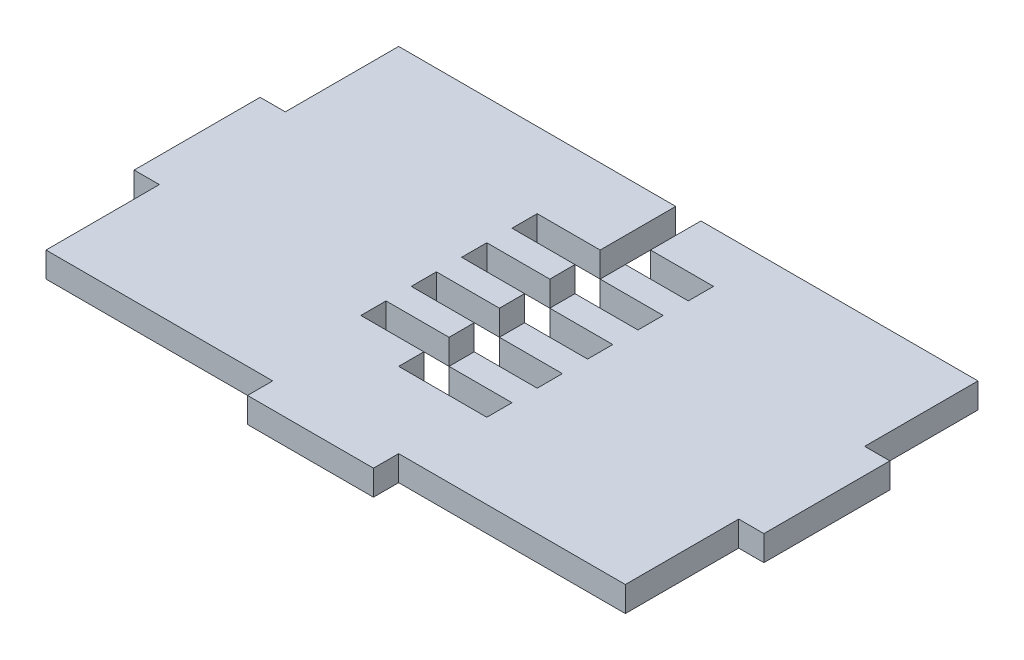
SolidWorks part; units mm, degrees
ref_plane "前视基准面" through (0, 0, 0) normal (0, 0, 1) x (1, 0, 0)
ref_plane "上视基准面" through (0, 0, 0) normal (0, 1, 0) x (1, 0, 0)
ref_plane "右视基准面" through (0, 0, 0) normal (1, 0, 0) x (0, 0, -1)
sketch "草图1" plane through (0, 0, 0) normal (0, 1, 0) x (1, 0, 0)
  line L1 (0, 0) -> (92, 0)
  line L2 (0, 0) -> (0, 56)
  line L3 (0, 56) -> (92, 56)
  line L4 (92, 0) -> (92, 56)
  line L5 (0, 38) -> (-4, 38)
  line L6 (0, 38) -> (0, 18)
  line L7 (0, 18) -> (-4, 18)
  line L8 (-4, 38) -> (-4, 18)
  line L9 (92, 38) -> (96, 38)
  line L10 (92, 38) -> (92, 18)
  line L11 (92, 18) -> (96, 18)
  line L12 (96, 38) -> (96, 18)
  line L13 (44, 56) -> (48, 56)
  line L14 (44, 56) -> (44, 12)
  line L15 (44, 12) -> (48, 12)
  line L16 (48, 56) -> (48, 12)
  line L22 (48, 34) -> (48, 36)
  line L34 (44, 44) -> (44, 40)
  line L42 (44, 28) -> (44, 24)
  line L45 (56, 0) -> (36, 0)
  line L46 (56, 0) -> (56, -4)
  line L47 (56, -4) -> (36, -4)
  line L48 (36, 0) -> (36, -4)
  line L50 (48, 24) -> (48, 12)
  line L53 (48, 16) -> (58, 16)
  line L54 (48, 16) -> (48, 12)
  line L55 (48, 12) -> (58, 12)
  line L56 (58, 16) -> (58, 12)
  line L57 (48, 20) -> (58, 20)
  line L58 (48, 20) -> (48, 24)
  line L59 (48, 24) -> (58, 24)
  line L60 (58, 20) -> (58, 24)
  line L61 (48, 32) -> (58, 32)
  line L62 (48, 32) -> (48, 28)
  line L63 (48, 28) -> (58, 28)
  line L64 (58, 32) -> (58, 28)
  line L65 (48, 40) -> (58, 40)
  line L66 (48, 40) -> (48, 36)
  line L67 (48, 36) -> (58, 36)
  line L68 (58, 40) -> (58, 36)
  line L69 (48, 48) -> (58, 48)
  line L70 (48, 48) -> (48, 44)
  line L71 (48, 44) -> (58, 44)
  line L72 (58, 48) -> (58, 44)
  line L73 (44, 44) -> (34, 44)
  line L74 (44, 44) -> (44, 40)
  line L75 (44, 40) -> (34, 40)
  line L76 (34, 44) -> (34, 40)
  line L77 (44, 36) -> (34, 36)
  line L78 (44, 36) -> (44, 32)
  line L79 (44, 32) -> (34, 32)
  line L80 (34, 36) -> (34, 32)
  line L81 (44, 28) -> (34, 28)
  line L82 (44, 28) -> (44, 24)
  line L83 (44, 24) -> (34, 24)
  line L84 (34, 28) -> (34, 24)
  line L85 (44, 20) -> (34, 20)
  line L86 (44, 20) -> (44, 16)
  line L87 (44, 16) -> (34, 16)
  line L88 (34, 20) -> (34, 16)
  point P5 (92, 28)
  point P6 (0, 28)
  point P7 (92, 38)
  point P8 (92, 20)
  point P9 (0, 38)
  point P10 (0, 20)
  point P19 (46, 56)
  point P20 (44, 56)
  point P21 (44, 56)
  point P26 (44, 44)
  point P27 (44, 48)
  point P28 (44, 36)
  point P29 (44, 40)
  point P30 (44, 32)
  point P31 (44, 28)
  point P32 (44, 24)
  point P33 (44, 12)
  point P34 (48, 24)
  point P35 (48, 28)
  point P36 (48, 32)
  point P37 (48, 36)
  point P38 (48, 44)
  point P39 (48, 48)
  point P41 (44, 20)
  point P42 (44, 16)
  point P43 (44, 12)
  point P44 (48, 16)
  point P46 (48, 20)
  point P55 (48, 40)
  point P68 (56, 0)
  point P69 (40, 0)
  point P70 (46, 0)
  point P89 (0, 0)
  point P90 (0, 0)
  point P91 (0, 0)
  point P92 (0, 0)
  point P93 (0, 0)
  point P94 (0, 0)
  point P95 (0, 0)
  point P96 (0, 0)
  point P97 (0, 0)
  point P98 (0, 0)
  point P99 (0, 0)
extrude "凸台-拉伸2" add sketch "草图1" along normal blind 4 contours L88 L85 L14 L83 L84 L81 L79 L80 L77 L75 L76 L73 L3 L2 L1 L4 L16 L69 L72 L71 L65 L68 L67 L61 L64 L63 L59 L60 L57 L50 L53 L56 L55 L15 L87 | L5 L8 L7 L2 | L1 L48 L47 L46 | L12 L9 L4 L11
